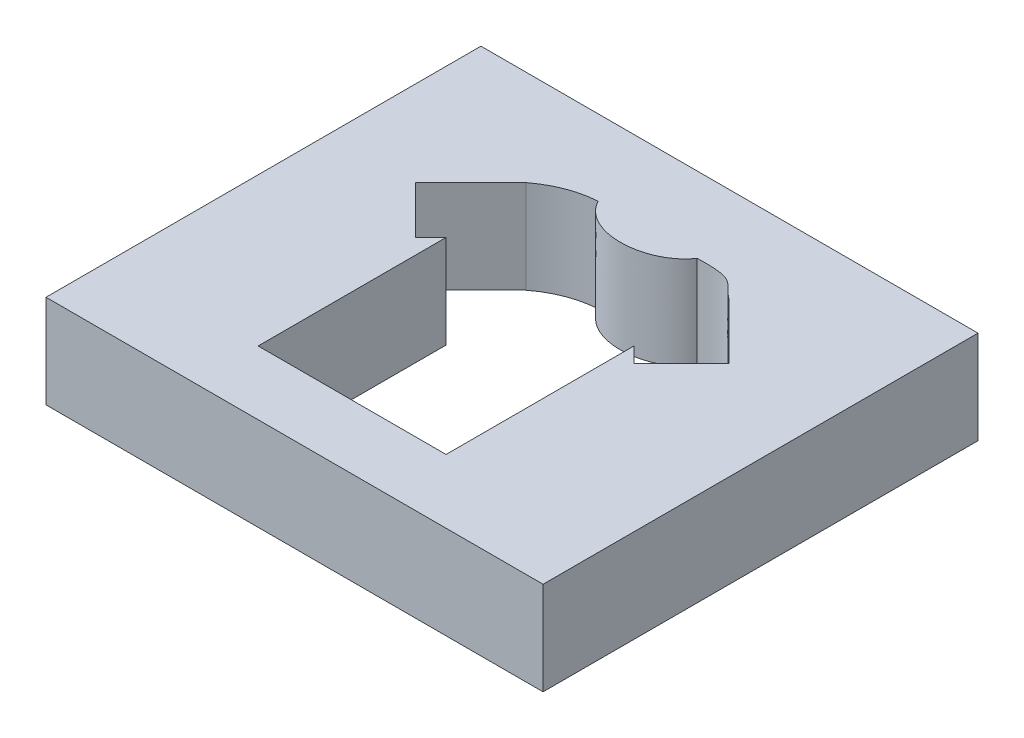
SolidWorks part; units mm, degrees
ref_plane "Front Plane" through (0, 0, 0) normal (0, 0, 1) x (1, 0, 0)
ref_plane "Top Plane" through (0, 0, 0) normal (0, 1, 0) x (1, 0, 0)
ref_plane "Right Plane" through (0, 0, 0) normal (1, 0, 0) x (0, 0, -1)
sketch "Sketch1" plane through (0, 0, 0) normal (0, 1, 0) x (1, 0, 0)
  line L1 (-42.8025, 22.3185) -> (-26.8025, 22.3185)
  line L2 (-42.8025, 22.3185) -> (-42.8025, 8.3185)
  line L3 (-42.8025, 8.3185) -> (-26.8025, 8.3185)
  line L4 (-26.8025, 22.3185) -> (-26.8025, 8.3185)
  line L63 (-40.0545, 17.4595) -> (-38.5247, 15.9296)
  line L64 (-38.5247, 15.9296) -> (-38.0304, 16.4239)
  line L65 (-38.0304, 16.4239) -> (-38.0304, 10.3751)
  line L66 (-38.0304, 10.3751) -> (-31.9816, 10.3751)
  line L67 (-31.9816, 10.3751) -> (-31.9816, 16.4239)
  line L68 (-31.9816, 16.4239) -> (-31.4873, 15.9296)
  line L69 (-31.4873, 15.9296) -> (-29.9575, 17.4595)
  line L70 (-29.9575, 17.4595) -> (-31.7345, 19.2365)
  line L71 (-40.0545, 17.4595) -> (-38.2775, 19.2365)
  spline S2 degree 2 poles (-38.2775, 19.2365) (-37.5291, 19.8135) (-36.5947, 19.8837) knots 0 0 0 1 1 1
  spline S3 degree 3 poles (-31.7345, 19.2365) (-32.318, 19.6645) (-32.0905, 19.9276) (-33.407, 19.8837) knots 0 0 0 0 1 1 1 1
  spline S4 degree 3 poles (-36.5947, 19.8837) (-36.0095, 18.7671) (-34.0743, 18.9001) (-33.407, 19.8837) knots 0 0 0 0 1 1 1 1
  dimension "D1" = 16
  dimension "D2" = 14
extrude "Boss-Extrude1" add sketch "Sketch1" along normal blind 3
